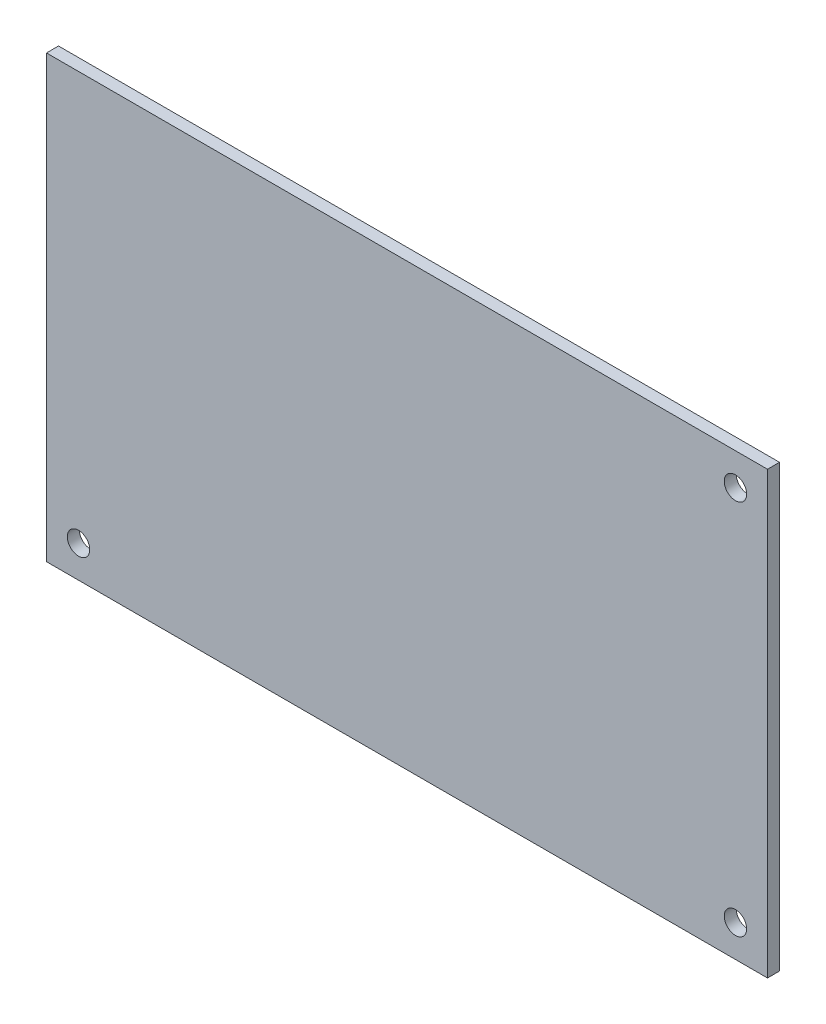
SolidWorks part; units mm, degrees
ref_plane "正面" through (0, 0, 0) normal (0, 0, 1) x (1, 0, 0)
ref_plane "平面" through (0, 0, 0) normal (0, 1, 0) x (1, 0, 0)
ref_plane "右側面" through (0, 0, 0) normal (1, 0, 0) x (0, 0, -1)
sketch "ｽｹｯﾁ1" plane through (0, 0, 0) normal (0, 0, 1) x (1, 0, 0)
  line L1 (-45, -27.5) -> (45, -27.5)
  line L2 (-45, -27.5) -> (-45, 27.5)
  line L3 (-45, 27.5) -> (45, 27.5)
  line L4 (45, -27.5) -> (45, 27.5)
  line L5 (-45, -27.5) -> (45, 27.5) construction
  line L6 (-45, 27.5) -> (45, -27.5) construction
  point P0 (0, 0)
  dimension "D1" = 90
  dimension "D2" = 55
extrude "ﾎﾞｽ - 押し出し1" add sketch "ｽｹｯﾁ1" along normal blind 1.5
sketch "ｽｹｯﾁ2" plane through (0, 0, 1.5) normal (0, 0, 1) x (1, 0, 0)
  line L0 (-45, 27.5) -> (-45, -27.5) construction
  line L1 (-45, -27.5) -> (45, -27.5) construction
  line L2 (45, -27.5) -> (45, 27.5) construction
  line L3 (45, 27.5) -> (-45, 27.5) construction
  circle A0 centre (41, -23.5) radius 1.4
  circle A1 centre (-41, -23.5) radius 1.4
  circle A2 centre (41, 23.5) radius 1.4
  dimension "D1" = 2.8
  dimension "D2" = 2.8
  dimension "D3" = 2.8
  dimension "D4" = 4
  dimension "D6" = 4
  dimension "D8" = 4
  dimension "D9" = 4
  dimension "D5" = 4
  dimension "D7" = 4
extrude "ｶｯﾄ - 押し出し1" cut sketch "ｽｹｯﾁ2" against normal blind 1.5
